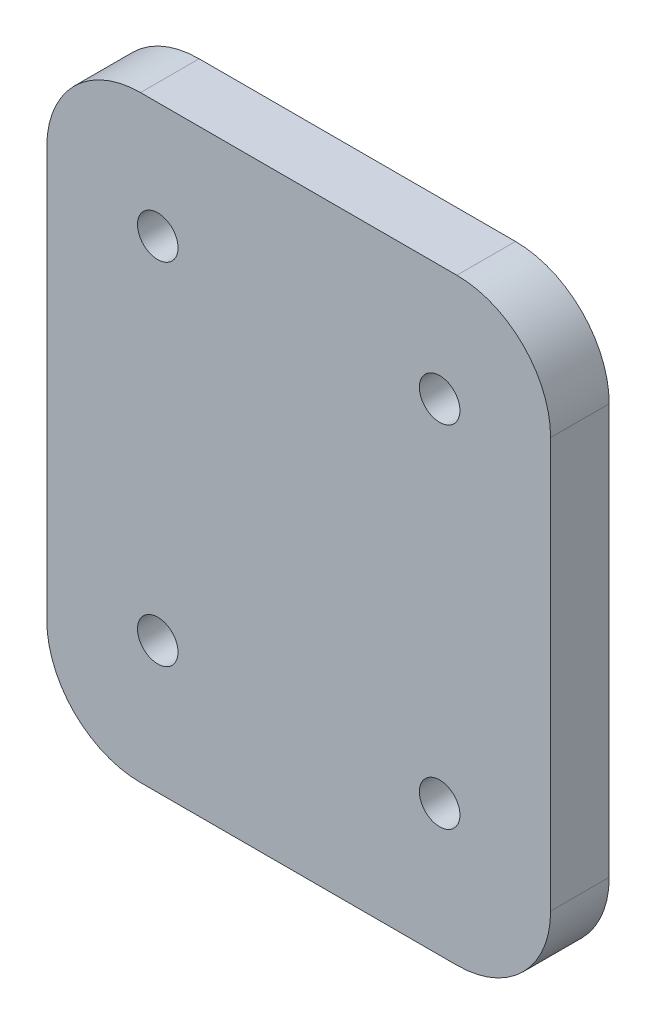
SolidWorks part; units mm, degrees
ref_plane "Front Plane" through (0, 0, 0) normal (0, 0, 1) x (1, 0, 0)
ref_plane "Top Plane" through (0, 0, 0) normal (0, 1, 0) x (1, 0, 0)
ref_plane "Right Plane" through (0, 0, 0) normal (1, 0, 0) x (0, 0, -1)
sketch "Sketch1" plane through (0, 0, 0) normal (0, 0, 1) x (1, 0, 0)
  line L1 (81.26, -26.2269) -> (54.26, -26.2269)
  line L2 (89.26, -18.2269) -> (89.26, 16.7731)
  line L3 (81.26, 24.7731) -> (54.26, 24.7731)
  line L4 (46.26, -18.2269) -> (46.26, 16.7731)
  line L5 (89.26, -26.2269) -> (46.26, 24.7731) construction
  line L6 (89.26, 24.7731) -> (46.26, -26.2269) construction
  arc A0 (54.26, 24.7731) -> (46.26, 16.7731) centre (54.26, 16.7731) ccw
  arc A1 (89.26, 16.7731) -> (81.26, 24.7731) centre (81.26, 16.7731) ccw
  arc A2 (81.26, -26.2269) -> (89.26, -18.2269) centre (81.26, -18.2269) ccw
  arc A3 (54.26, -26.2269) -> (46.26, -18.2269) centre (54.26, -18.2269) cw
  circle A4 centre (79.79, 14.895) radius 1.73
  circle A5 centre (55.73, 14.895) radius 1.73
  circle A6 centre (55.73, -14.995) radius 1.73
  circle A7 centre (79.79, -14.995) radius 1.73
  point P0 (67.76, -0.7269)
  dimension "D3" = 24.06
  dimension "D4" = 24.06
  dimension "D5" = 29.89
  dimension "D6" = 29.89
  dimension "D7" = 8
  dimension "D8" = 3.46
  dimension "D9" = 3.46
  dimension "D10" = 3.46
  dimension "D11" = 3.46
  dimension "D1" = 43
  dimension "D2" = 51
extrude "Boss-Extrude1" add sketch "Sketch1" along normal blind 5
